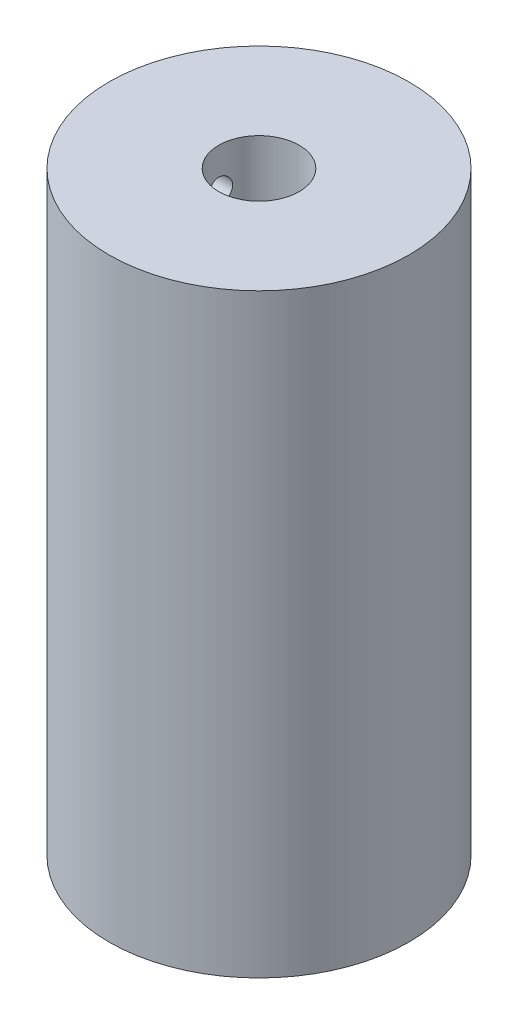
SolidWorks part; units mm, degrees
ref_plane "Front Plane" through (0, 0, 0) normal (0, 0, 1) x (1, 0, 0)
ref_plane "Top Plane" through (0, 0, 0) normal (0, 1, 0) x (1, 0, 0)
ref_plane "Right Plane" through (0, 0, 0) normal (1, 0, 0) x (0, 0, -1)
sketch "Sketch1" plane through (0, 0, 0) normal (0, 1, 0) x (1, 0, 0)
  circle A0 centre (0, 0) radius 18.6431
extrude "40mm arm" add sketch "Sketch1" along normal blind 41
sketch "Sketch2" plane through (0, 41, 0) normal (0, 1, 0) x (1, 0, 0)
  circle A0 centre (0, 0) radius 5
  dimension "D1" = 10
extrude "10mm hole, 10mm deep" cut sketch "Sketch2" against normal blind 10
sketch "Sketch3" plane through (0, 0, 0) normal (1, 0, 0) x (0, 0, -1)
  line L0 (0, 0) -> (0, 42.1117) construction
  circle A0 centre (0, 36.0596) radius 1.5
  dimension "D1" = 3
extrude "0.01m screw hole" cut sketch "Sketch3" against normal blind 25
sketch "Sketch4" plane through (0, 0, 0) normal (0, -1, 0) x (1, 0, 0)
  circle A0 centre (0, 0) radius 5
  dimension "D1" = 10
sketch "Sketch5" plane through (0, 0, 0) normal (0, -1, 0) x (1, 0, 0)
  circle A0 centre (0, 0) radius 18.6431
extrude "Boss-Extrude1" add sketch "Sketch5" along normal blind 33
extrude "Cut-Extrude2" cut sketch "Sketch4" along normal blind 92
